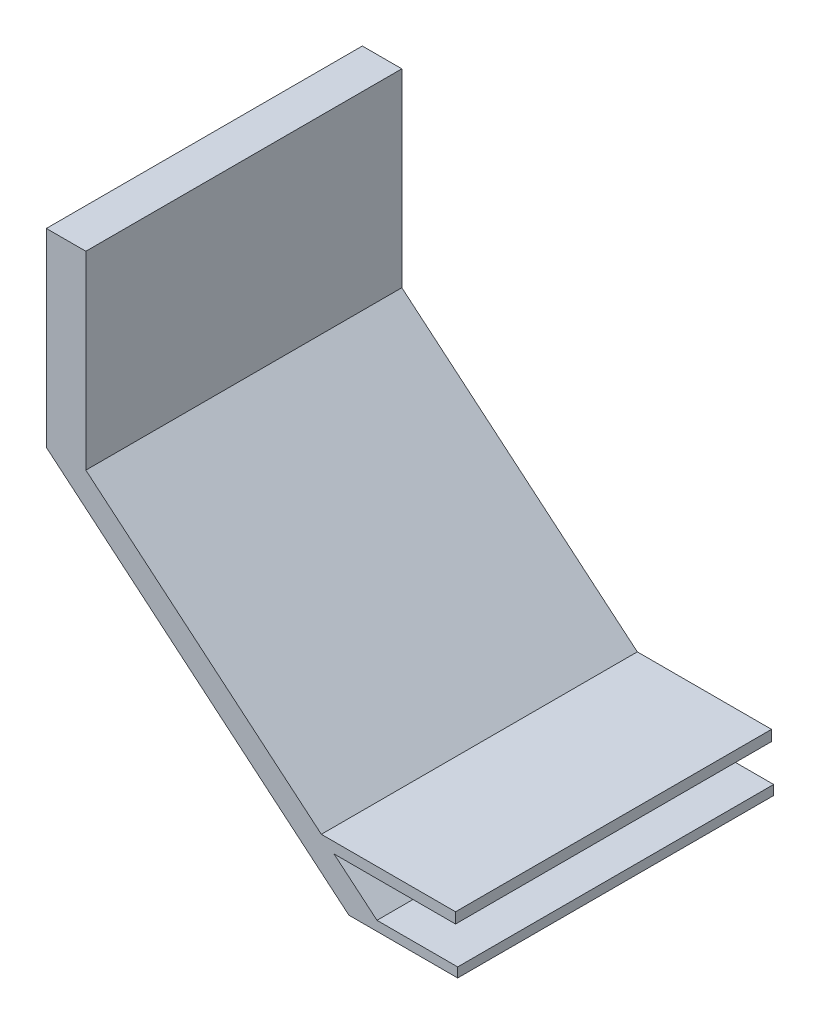
SolidWorks part; units mm, degrees
ref_plane "Front Plane" through (0, 0, 0) normal (0, 0, 1) x (1, 0, 0)
ref_plane "Top Plane" through (0, 0, 0) normal (0, 1, 0) x (1, 0, 0)
ref_plane "Right Plane" through (0, 0, 0) normal (1, 0, 0) x (0, 0, -1)
sketch "Sketch1" plane through (0, 0, 0) normal (0, 0, 1) x (1, 0, 0)
  line L0 (0, 0) -> (0, -120)
  line L1 (0, -120) -> (191.5111, -280.6969)
  line L2 (191.5111, -280.6969) -> (235.3446, -280.6969)
  line L3 (157.072, -251.7991) -> (233.9903, -251.7991)
  line L4 (233.9903, -251.7991) -> (233.9903, -245.0689)
  line L5 (233.9903, -245.0689) -> (149.0513, -245.0689)
  line L6 (235.3446, -280.6969) -> (235.3446, -274.6141)
  line L7 (235.3446, -274.6141) -> (184.2619, -274.6141)
  line L8 (0, 0) -> (-25, 0)
  line L9 (-25, 0) -> (-25, -120)
  line L10 (-25, -120) -> (166.5111, -280.6969)
  line L11 (166.5111, -280.6969) -> (191.5111, -280.6969)
  line L12 (-25, -120) -> (0, -120)
  line L13 (157.072, -251.7991) -> (149.0513, -245.0689)
  line L14 (191.5111, -280.6969) -> (184.2619, -274.6141)
extrude "Boss-Extrude4" add sketch "Sketch1" along normal blind 200 contours L9 L12 L0 L8 | L12 L10 L11 L1 | L5 L13 L3 L4 | L2 L6 L7 L14
